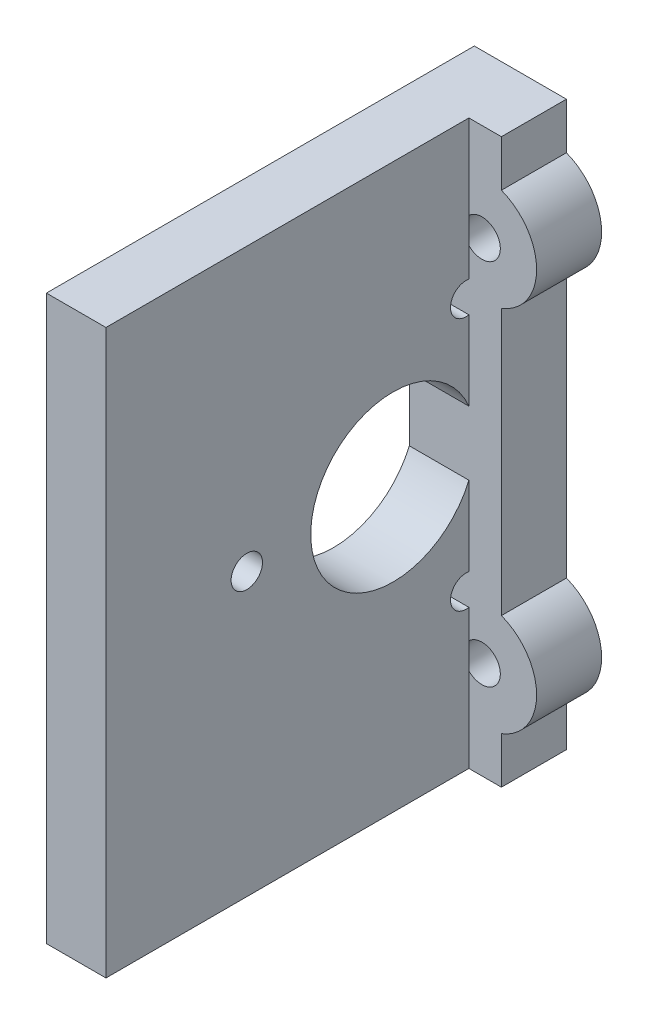
SolidWorks part; units mm, degrees
ref_plane "Front Plane" through (0, 0, 0) normal (0, 0, 1) x (1, 0, 0)
ref_plane "Top Plane" through (0, 0, 0) normal (0, 1, 0) x (1, 0, 0)
ref_plane "Right Plane" through (0, 0, 0) normal (1, 0, 0) x (0, 0, -1)
ref_plane "Plane1" through (264, 0, 0) normal (1, 0, 0) x (0, 0, -1)
sketch "Sketch1" plane through (264, 0, 0) normal (1, 0, 0) x (0, 0, -1)
  line L0 (-287, 274) -> (-326.5, 274)
  line L1 (-326.5, 274) -> (-326.5, 326)
  line L2 (-326.5, 326) -> (-287, 326)
  line L3 (-287, 326) -> (-287, 274)
  circle A0 centre (-313.5, 300) radius 1.45
  circle A1 centre (-293.25, 311.6913) radius 1.45
  circle A2 centre (-293.25, 288.3087) radius 1.45
extrude "Boss-Extrude1" add sketch "Sketch1" along normal blind 5.5
sketch "Sketch2" plane through (264, 0, 0) normal (1, 0, 0) x (0, 0, -1)
  circle A0 centre (-300, 300) radius 7.6
extrude "Cut-Extrude1" cut sketch "Sketch2" along normal blind 5.5
ref_plane "Plane2" through (0, 0, 287) normal (0, 0, 1) x (1, 0, 0)
sketch "Sketch3" plane through (0, 0, 287) normal (0, 0, 1) x (1, 0, 0)
  line L0 (264, 274) -> (272.5, 274)
  line L1 (272.5, 274) -> (272.5, 326)
  line L2 (272.5, 326) -> (264, 326)
  line L3 (264, 326) -> (264, 274)
extrude "Boss-Extrude2" add sketch "Sketch3" along normal blind 6
sketch "Sketch4" plane through (0, 0, 287) normal (0, 0, 1) x (1, 0, 0)
  circle A0 centre (270.7, 283) radius 5.05
  circle A1 centre (270.7, 283) radius 1.7
extrude "Boss-Extrude3" add sketch "Sketch4" along normal blind 6
sketch "Sketch5" plane through (0, 0, 287) normal (0, 0, 1) x (1, 0, 0)
  circle A0 centre (270.7, 317) radius 5.05
  circle A1 centre (270.7, 317) radius 1.7
extrude "Boss-Extrude4" add sketch "Sketch5" along normal blind 6
sketch "Sketch6" plane through (0, 0, 287) normal (0, 0, 1) x (1, 0, 0)
  circle A0 centre (270.7, 283) radius 1.7
  circle A1 centre (270.7, 317) radius 1.7
extrude "Cut-Extrude2" cut sketch "Sketch6" along normal blind 6
